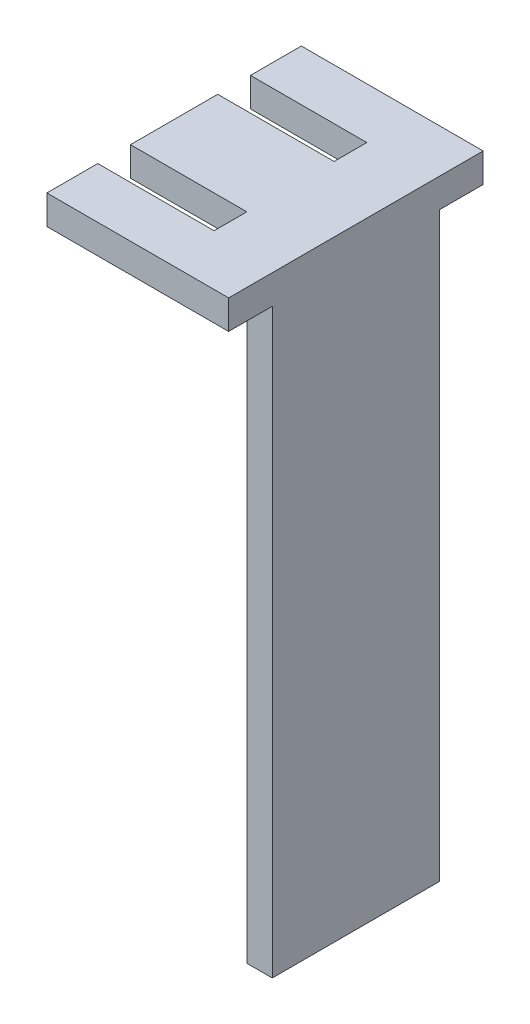
SolidWorks part; units mm, degrees
ref_plane "Front Plane" through (0, 0, 0) normal (0, 0, 1) x (1, 0, 0)
ref_plane "Top Plane" through (0, 0, 0) normal (0, 1, 0) x (1, 0, 0)
ref_plane "Right Plane" through (0, 0, 0) normal (1, 0, 0) x (0, 0, -1)
sketch "Sketch1" plane through (0, 0, 0) normal (0, 1, 0) x (1, 0, 0)
  line L1 (-9.8517, 12.6589) -> (15.1483, 12.6589)
  line L2 (-9.8517, 12.6589) -> (-9.8517, -22.3411)
  line L3 (-9.8517, -22.3411) -> (15.1483, -22.3411)
  line L4 (15.1483, 12.6589) -> (15.1483, -22.3411)
  dimension "D1" = 25
  dimension "D2" = 35
extrude "Boss-Extrude1" add sketch "Sketch1" along normal blind 4
sketch "Sketch2" plane through (0, 4, 0) normal (0, 1, 0) x (1, 0, 0)
  line L0 (-9.8517, 12.6589) -> (-9.8517, -22.3411) construction
  line L1 (-9.8517, -10.8411) -> (6.1483, -10.8411)
  line L2 (-9.8517, -10.8411) -> (-9.8517, -15.3411)
  line L3 (-9.8517, -15.3411) -> (6.1483, -15.3411)
  line L4 (6.1483, -10.8411) -> (6.1483, -15.3411)
  line L5 (-9.8517, -22.3411) -> (15.1483, -22.3411) construction
  line L7 (15.1483, 12.6589) -> (-9.8517, 12.6589) construction
  line L8 (-9.8517, 5.6589) -> (6.1483, 5.6589)
  line L9 (-9.8517, 5.6589) -> (-9.8517, 1.1589)
  line L10 (-9.8517, 1.1589) -> (6.1483, 1.1589)
  line L11 (6.1483, 5.6589) -> (6.1483, 1.1589)
  dimension "D1" = 16
  dimension "D2" = 4.5
  dimension "D3" = 7
  dimension "D4" = 4.5
  dimension "D5" = 16
  dimension "D6" = 7
extrude "Cut-Extrude1" cut sketch "Sketch2" against normal blind 4
sketch "Sketch3" plane through (0, 0, 0) normal (0, -1, 0) x (-1, 0, 0)
  line L0 (-15.1483, -22.3411) -> (-15.1483, 12.6589) construction
  line L1 (-11.6483, -16.3411) -> (-15.1483, -16.3411)
  line L2 (-11.6483, -16.3411) -> (-11.6483, 6.6589)
  line L3 (-11.6483, 6.6589) -> (-15.1483, 6.6589)
  line L4 (-15.1483, -16.3411) -> (-15.1483, 6.6589)
  line L5 (9.8517, -22.3411) -> (-15.1483, -22.3411) construction
  dimension "D1" = 23
  dimension "D2" = 3.5
  dimension "D3" = 6
extrude "Boss-Extrude2" add sketch "Sketch3" along normal blind 80
